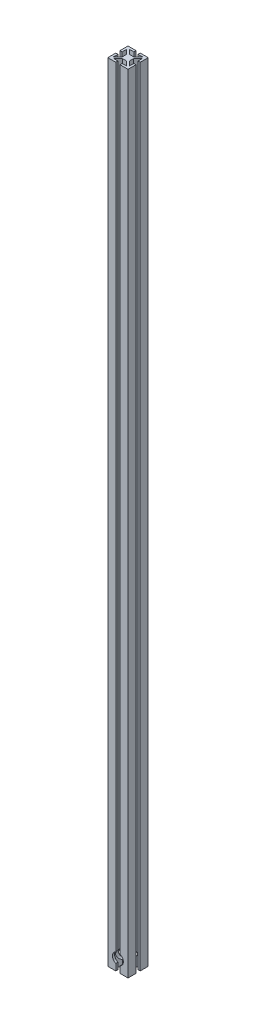
SolidWorks part; units mm, degrees
ref_plane "Front Plane" through (0, 0, 0) normal (0, 0, 1) x (1, 0, 0)
ref_plane "Top Plane" through (0, 0, 0) normal (0, 1, 0) x (1, 0, 0)
ref_plane "Right Plane" through (0, 0, 0) normal (1, 0, 0) x (0, 0, -1)
sketch "Sketch2" plane through (0.5947, 0, 0.5947) normal (0, 1, 0) x (1, 0, 0)
  line L0 (-0.5947, 0.5947) -> (-0.5947, 20.2394) construction
  line L1 (-0.5947, 0.5947) -> (-20.2394, 0.5947) construction
  line L2 (-0.5947, 0.5947) -> (-20.2394, 20.2394) construction
  line L3 (-19.6447, 19.6447) -> (-4.6587, 19.6447)
  line L4 (-4.6587, 19.6447) -> (-4.6587, 15.5807)
  line L5 (-4.6587, 15.5807) -> (-12.707, 15.5807)
  line L6 (-12.707, 15.5807) -> (-4.4774, 7.3511)
  line L7 (-4.4774, 7.3511) -> (3.288, 7.3511)
  line L8 (-19.6447, 19.6447) -> (-19.6447, 4.6587)
  line L9 (-19.6447, 4.6587) -> (-15.5807, 4.6587)
  line L10 (-15.5807, 4.6587) -> (-15.5807, 12.707)
  line L11 (-15.5807, 12.707) -> (-7.3511, 4.4774)
  line L12 (-7.3511, 4.4774) -> (-7.3511, -3.288)
  line L13 (-4.4774, -6.1617) -> (3.288, -6.1617)
  line L14 (-12.707, -14.3913) -> (-4.4774, -6.1617)
  line L15 (-4.6587, -14.3913) -> (-12.707, -14.3913)
  line L16 (-4.6587, -18.4553) -> (-4.6587, -14.3913)
  line L17 (-19.6447, -18.4553) -> (-4.6587, -18.4553)
  line L18 (-19.6447, -18.4553) -> (-19.6447, -3.4693)
  line L19 (-19.6447, -3.4693) -> (-15.5807, -3.4693)
  line L20 (-15.5807, -3.4693) -> (-15.5807, -11.5176)
  line L21 (-15.5807, -11.5176) -> (-7.3511, -3.288)
  line L22 (11.5176, 15.5807) -> (3.288, 7.3511)
  line L23 (3.4693, 15.5807) -> (11.5176, 15.5807)
  line L24 (3.4693, 19.6447) -> (3.4693, 15.5807)
  line L25 (18.4553, 19.6447) -> (3.4693, 19.6447)
  line L26 (18.4553, 19.6447) -> (18.4553, 4.6587)
  line L27 (18.4553, 4.6587) -> (14.3913, 4.6587)
  line L28 (14.3913, 4.6587) -> (14.3913, 12.707)
  line L29 (14.3913, 12.707) -> (6.1617, 4.4774)
  line L30 (6.1617, 4.4774) -> (6.1617, -3.288)
  line L31 (14.3913, -11.5176) -> (6.1617, -3.288)
  line L32 (14.3913, -3.4693) -> (14.3913, -11.5176)
  line L33 (18.4553, -3.4693) -> (14.3913, -3.4693)
  line L34 (18.4553, -18.4553) -> (18.4553, -3.4693)
  line L35 (18.4553, -18.4553) -> (3.4693, -18.4553)
  line L36 (3.4693, -18.4553) -> (3.4693, -14.3913)
  line L37 (3.4693, -14.3913) -> (11.5176, -14.3913)
  line L38 (11.5176, -14.3913) -> (3.288, -6.1617)
  point P26 (-7.3511, 0.5947)
  point P27 (-0.5947, 7.3511)
  point P44 (-0.5947, -6.1617)
  dimension "D1" = 38.1
  dimension "D2" = 8.128
  dimension "D3" = 13.5128
  dimension "D4" = 4.064
  dimension "D5" = 4.064
extrude "Boss-Extrude1" add sketch "Sketch2" along normal up to surface (1485.9 mm away)
other "1515<1>"
sketch "Sketch3" plane through (0, 0, -19.05) normal (0, 0, -1) x (-1, 0, 0)
  line L0 (-19.05, 0) -> (-4.064, 0) construction
  circle A0 centre (0, 21.844) radius 10.287
  dimension "D1" = 20.574
  dimension "D2" = 21.844
extrude "Cut-Extrude1" cut sketch "Sketch3" against normal blind 16.51
mirror "Mirror1" about plane through (0, 0, 0) normal (0, 0, 1) of "Cut-Extrude1"
